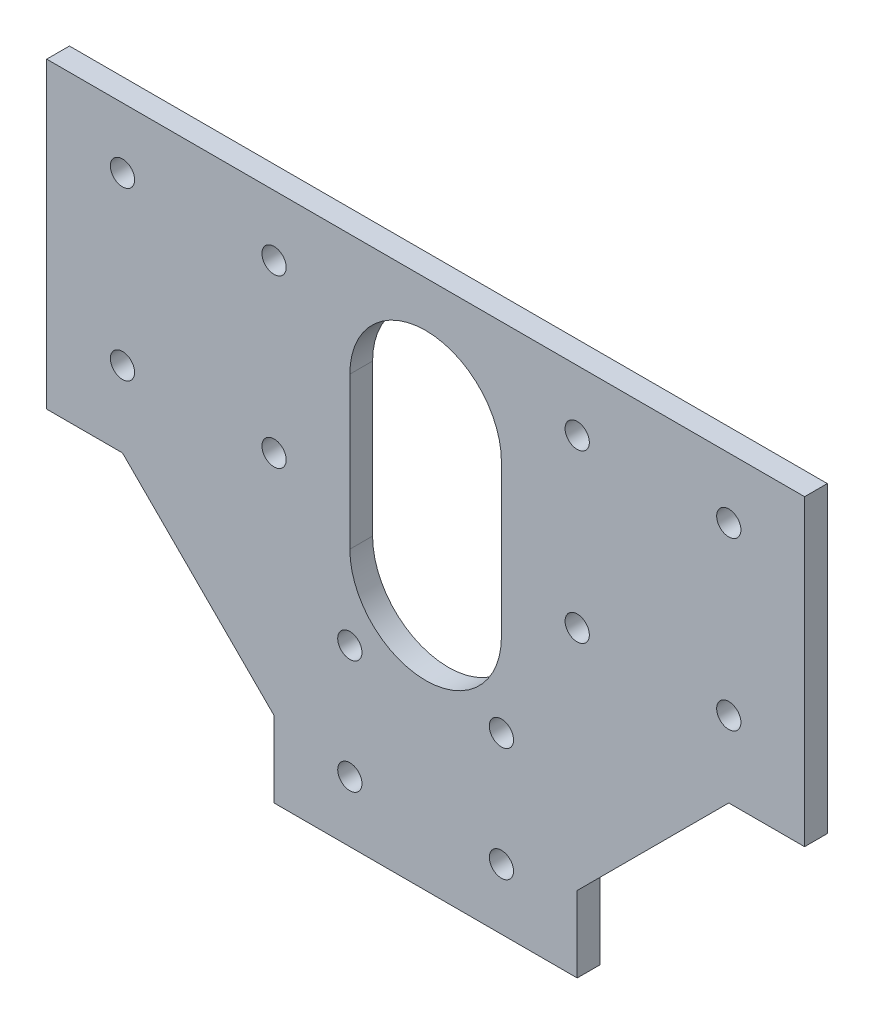
SolidWorks part; units mm, degrees
material "Thornel VCB-20 碳布"
ref_plane "前视基准面" through (0, 0, 0) normal (0, 0, 1) x (1, 0, 0)
ref_plane "上视基准面" through (0, 0, 0) normal (0, 1, 0) x (1, 0, 0)
ref_plane "右视基准面" through (0, 0, 0) normal (1, 0, 0) x (0, 0, -1)
other "Configuration Table"
sketch "草图1" plane through (0, 0, 0) normal (0, 0, 1) x (1, 0, 0)
  line L0 (-20, 0) -> (-30, 0)
  line L1 (-30, 0) -> (-30, 40)
  line L2 (-30, 40) -> (70, 40)
  line L3 (70, 40) -> (70, 0)
  line L4 (70, 0) -> (60, 0)
  line L5 (40, -20) -> (40, -30)
  line L6 (40, -30) -> (0, -30)
  line L7 (0, -30) -> (0, -20)
  line L8 (-20, 0) -> (0, -20)
  line L9 (40, -20) -> (60, 0)
  line L10 (40, -20) -> (40, 0) construction
  line L11 (40, 0) -> (60, 0) construction
  line L12 (-20, 0) -> (0, 0) construction
  line L13 (0, 0) -> (0, -20)
  dimension "D1" = 40
  dimension "D2" = 40
  dimension "D3" = 45
  dimension "D4" = 45
  dimension "D5" = 30
  dimension "D6" = 30
  dimension "D7" = 30
  dimension "D8" = 20
  dimension "D9" = 20
extrude "凸台-拉伸1" add sketch "草图1" along normal blind 3
sketch "草图2" plane through (0, 0, 3) normal (0, 0, 1) x (1, 0, 0)
  line L0 (10, -7) -> (30, -7) construction
  line L1 (30, -7) -> (30, -22) construction
  line L2 (30, -22) -> (10, -22) construction
  line L3 (10, -22) -> (10, -7) construction
  line L4 (-20, 10) -> (60, 10) construction
  line L5 (60, 10) -> (60, 32) construction
  line L6 (60, 32) -> (-20, 32) construction
  line L7 (-20, 32) -> (-20, 10) construction
  line L10 (-20, 0) -> (0, -20)
  line L11 (0, -20) -> (0, -30)
  line L12 (0, -30) -> (40, -30)
  line L13 (40, -30) -> (40, -20)
  line L14 (40, -20) -> (60, 0)
  line L15 (60, 0) -> (70, 0)
  line L16 (70, 0) -> (70, 40)
  line L17 (70, 40) -> (-30, 40)
  line L18 (-30, 40) -> (-30, 0)
  line L19 (-30, 0) -> (-20, 0)
  line L20 (-20, 0) -> (0, -20) construction
  line L21 (0, -20) -> (0, -30) construction
  line L22 (0, -30) -> (40, -30) construction
  line L23 (40, -30) -> (40, -20) construction
  line L24 (40, -20) -> (60, 0) construction
  line L25 (60, 0) -> (70, 0) construction
  line L26 (70, 0) -> (70, 40) construction
  line L27 (70, 40) -> (-30, 40) construction
  line L28 (-30, 40) -> (-30, 0) construction
  line L29 (-30, 0) -> (-20, 0) construction
  circle A0 centre (10, -7) radius 1.6
  circle A1 centre (30, -7) radius 1.6
  circle A2 centre (10, -22) radius 1.6
  circle A3 centre (30, -22) radius 1.6
  circle A4 centre (-20, 10) radius 1.6
  circle A5 centre (-20, 32) radius 1.6
  circle A6 centre (0, 10) radius 1.6
  circle A7 centre (40, 10) radius 1.6
  circle A8 centre (60, 10) radius 1.6
  circle A9 centre (60, 32) radius 1.6
  circle A10 centre (40, 32) radius 1.6
  circle A11 centre (0, 32) radius 1.6
  dimension "D2" = 3.2
  dimension "D3" = 20
  dimension "D4" = 10
  dimension "D5" = 7
  dimension "D6" = 15
  dimension "D7" = 10
  dimension "D8" = 10
  dimension "D9" = 8
  dimension "D10" = 10
  dimension "D11" = 20
  dimension "D12" = 20
  dimension "D13" = 20
  dimension "D14" = 20
  dimension "D1" = 0
extrude "切除-拉伸1" cut sketch "草图2" against normal blind 3
sketch "草图3" plane through (0, 0, 3) normal (0, 0, 1) x (1, 0, 0)
  line L0 (-30, 40) -> (70, 40) construction
  line L1 (20, 40) -> (20, -30) construction
  line L2 (40, -30) -> (0, -30) construction
  line L3 (20, 24) -> (20, 4) construction
  line L4 (30, 24) -> (30, 4)
  line L5 (10, 24) -> (10, 4)
  arc A0 (30, 24) -> (10, 24) centre (20, 24) ccw
  arc A1 (10, 4) -> (30, 4) centre (20, 4) ccw
  point P8 (20, 14)
  dimension "D1" = 10
  dimension "D2" = 20
  dimension "D3" = 26
extrude "切除-拉伸2" cut sketch "草图3" against normal through all
